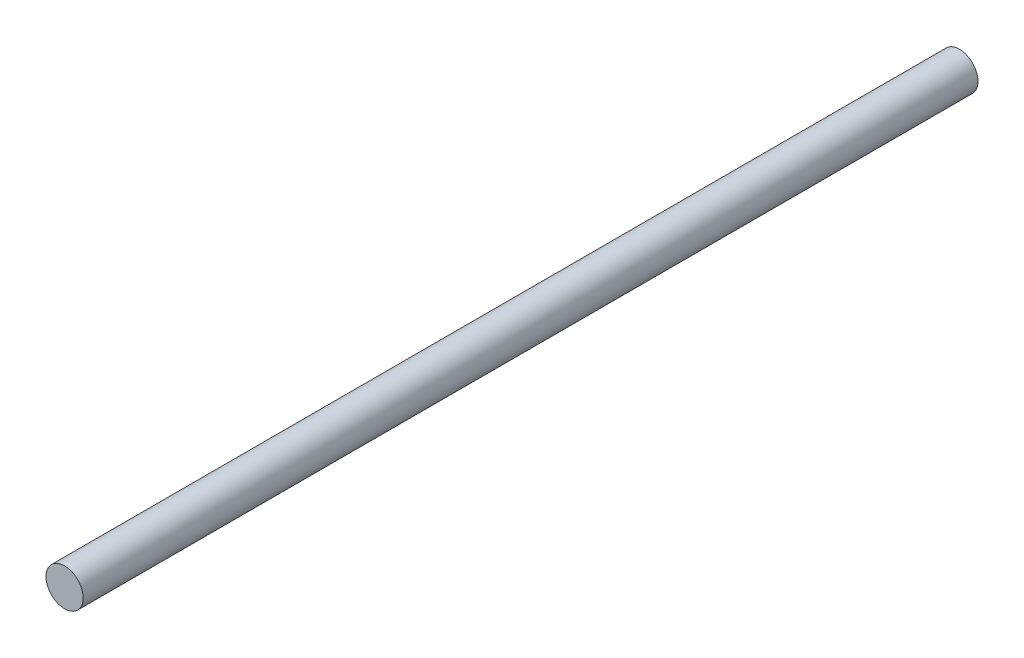
SolidWorks part; units mm, degrees
ref_plane "Front Plane" through (0, 0, 0) normal (0, 0, 1) x (1, 0, 0)
ref_plane "Top Plane" through (0, 0, 0) normal (0, 1, 0) x (1, 0, 0)
ref_plane "Right Plane" through (0, 0, 0) normal (1, 0, 0) x (0, 0, -1)
sketch "Sketch1" plane through (0, 0, 0) normal (0, 0, 1) x (1, 0, 0)
  circle A0 centre (0, 0) radius 9.35
  dimension "D1" = 18.7
extrude "Boss-Extrude1" add sketch "Sketch1" along normal blind 450
